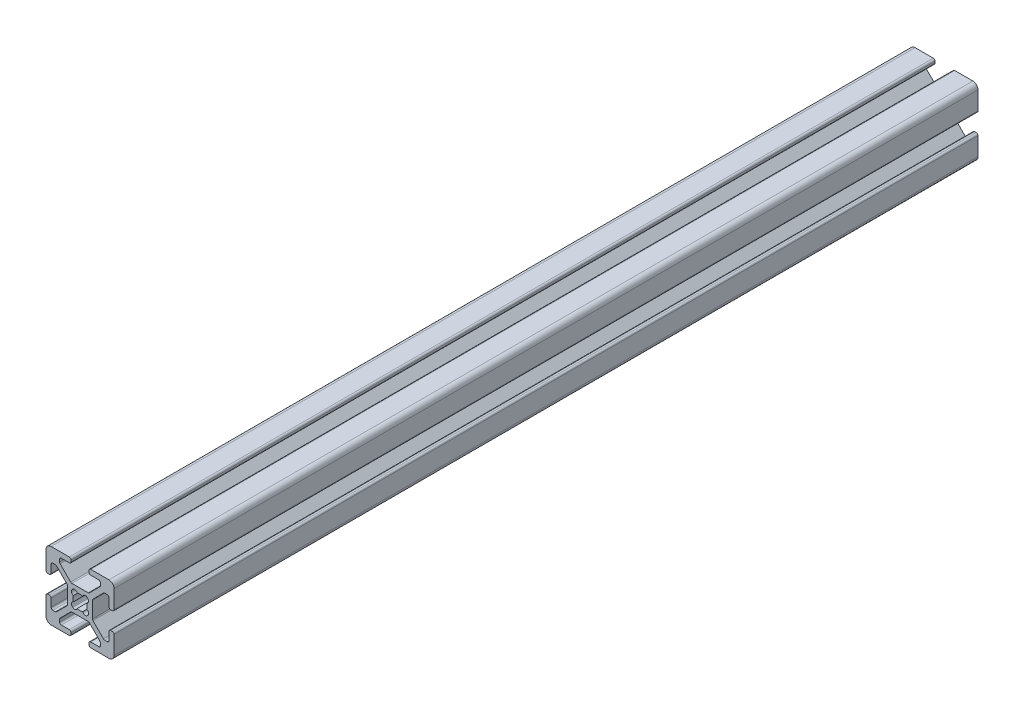
SolidWorks part; units mm, degrees
material "1060 Alloy"
ref_plane "Front Plane" through (0, 0, 0) normal (0, 0, 1) x (1, 0, 0)
ref_plane "Top Plane" through (0, 0, 0) normal (0, 1, 0) x (1, 0, 0)
ref_plane "Right Plane" through (0, 0, 0) normal (1, 0, 0) x (0, 0, -1)
sketch "Sketch2" plane through (0, 0, 0) normal (0, 0, 1) x (1, 0, 0)
  line L0 (-10, -3.138) -> (-10, -8.5)
  line L1 (-8.5, -10) -> (-3.138, -10)
  line L2 (-2.63, -9.492) -> (-2.63, -9.008)
  line L3 (-3.138, -8.5) -> (-5.487, -8.5)
  line L4 (-5.995, -7.992) -> (-5.995, -7.2662)
  line L5 (-5.8462, -6.907) -> (-2.743, -3.8038)
  line L6 (-2.3838, -3.655) -> (2.3841, -3.655)
  line L7 (2.7433, -3.8038) -> (5.8462, -6.9067)
  line L8 (5.995, -7.2659) -> (5.995, -7.992)
  line L9 (5.487, -8.5) -> (3.138, -8.5)
  line L10 (2.63, -9.008) -> (2.63, -9.492)
  line L11 (3.138, -10) -> (8.5, -10)
  line L12 (10, -8.5) -> (10, -3.138)
  line L13 (9.492, -2.63) -> (9.008, -2.63)
  line L14 (8.5, -3.138) -> (8.5, -5.487)
  line L15 (7.992, -5.995) -> (7.2662, -5.995)
  line L16 (6.907, -5.8462) -> (3.8038, -2.743)
  line L17 (3.655, -2.3838) -> (3.655, 2.3841)
  line L18 (3.8038, 2.7433) -> (6.9067, 5.8462)
  line L19 (7.2659, 5.995) -> (7.992, 5.995)
  line L20 (8.5, 5.487) -> (8.5, 3.138)
  line L21 (9.008, 2.63) -> (9.492, 2.63)
  line L22 (10, 3.138) -> (10, 8.5)
  line L23 (8.5, 10) -> (3.138, 10)
  line L24 (2.63, 9.492) -> (2.63, 9.008)
  line L25 (3.138, 8.5) -> (5.487, 8.5)
  line L26 (5.995, 7.992) -> (5.995, 7.2662)
  line L27 (5.8462, 6.907) -> (2.743, 3.8038)
  line L28 (2.3838, 3.655) -> (-2.3841, 3.655)
  line L29 (-2.7433, 3.8038) -> (-5.8462, 6.9067)
  line L30 (-5.995, 7.2659) -> (-5.995, 7.992)
  line L31 (-5.487, 8.5) -> (-3.138, 8.5)
  line L32 (-2.63, 9.008) -> (-2.63, 9.492)
  line L33 (-3.138, 10) -> (-8.5, 10)
  line L34 (-10, 8.5) -> (-10, 3.138)
  line L35 (-9.492, 2.63) -> (-9.008, 2.63)
  line L36 (-8.5, 3.138) -> (-8.5, 5.487)
  line L37 (-7.992, 5.995) -> (-7.2662, 5.995)
  line L38 (-6.907, 5.8462) -> (-3.8038, 2.743)
  line L39 (-3.655, 2.3838) -> (-3.655, -2.3841)
  line L40 (-3.8038, -2.7433) -> (-6.9067, -5.8462)
  line L41 (-7.2659, -5.995) -> (-7.992, -5.995)
  line L42 (-8.5, -5.487) -> (-8.5, -3.138)
  line L43 (-9.008, -2.63) -> (-9.492, -2.63)
  line L44 (-2.1245, 2.3045) -> (-2.3045, 2.1245)
  line L45 (2.3045, 2.1245) -> (2.1245, 2.3045)
  line L46 (2.1245, -2.3045) -> (2.3045, -2.1245)
  line L47 (-2.3045, -2.1245) -> (-2.1245, -2.3045)
  arc A0 (-10, -8.5) -> (-8.5, -10) centre (-8.5, -8.5) ccw
  arc A1 (-3.138, -10) -> (-2.63, -9.492) centre (-3.138, -9.492) ccw
  arc A2 (-2.63, -9.008) -> (-3.138, -8.5) centre (-3.138, -9.008) ccw
  arc A3 (-5.995, -7.992) -> (-5.487, -8.5) centre (-5.487, -7.992) ccw
  arc A4 (-5.8462, -6.907) -> (-5.995, -7.2662) centre (-5.487, -7.2662) ccw
  arc A5 (-2.3838, -3.655) -> (-2.743, -3.8038) centre (-2.3838, -4.163) ccw
  arc A6 (2.7433, -3.8038) -> (2.3841, -3.655) centre (2.3841, -4.163) ccw
  arc A7 (5.995, -7.2659) -> (5.8462, -6.9067) centre (5.487, -7.2659) ccw
  arc A8 (5.487, -8.5) -> (5.995, -7.992) centre (5.487, -7.992) ccw
  arc A9 (3.138, -8.5) -> (2.63, -9.008) centre (3.138, -9.008) ccw
  arc A10 (2.63, -9.492) -> (3.138, -10) centre (3.138, -9.492) ccw
  arc A11 (8.5, -10) -> (10, -8.5) centre (8.5, -8.5) ccw
  arc A12 (10, -3.138) -> (9.492, -2.63) centre (9.492, -3.138) ccw
  arc A13 (9.008, -2.63) -> (8.5, -3.138) centre (9.008, -3.138) ccw
  arc A14 (7.992, -5.995) -> (8.5, -5.487) centre (7.992, -5.487) ccw
  arc A15 (6.907, -5.8462) -> (7.2662, -5.995) centre (7.2662, -5.487) ccw
  arc A16 (3.655, -2.3838) -> (3.8038, -2.743) centre (4.163, -2.3838) ccw
  arc A17 (3.8038, 2.7433) -> (3.655, 2.3841) centre (4.163, 2.3841) ccw
  arc A18 (7.2659, 5.995) -> (6.9067, 5.8462) centre (7.2659, 5.487) ccw
  arc A19 (8.5, 5.487) -> (7.992, 5.995) centre (7.992, 5.487) ccw
  arc A20 (8.5, 3.138) -> (9.008, 2.63) centre (9.008, 3.138) ccw
  arc A21 (9.492, 2.63) -> (10, 3.138) centre (9.492, 3.138) ccw
  arc A22 (10, 8.5) -> (8.5, 10) centre (8.5, 8.5) ccw
  arc A23 (3.138, 10) -> (2.63, 9.492) centre (3.138, 9.492) ccw
  arc A24 (2.63, 9.008) -> (3.138, 8.5) centre (3.138, 9.008) ccw
  arc A25 (5.995, 7.992) -> (5.487, 8.5) centre (5.487, 7.992) ccw
  arc A26 (5.8462, 6.907) -> (5.995, 7.2662) centre (5.487, 7.2662) ccw
  arc A27 (2.3838, 3.655) -> (2.743, 3.8038) centre (2.3838, 4.163) ccw
  arc A28 (-2.7433, 3.8038) -> (-2.3841, 3.655) centre (-2.3841, 4.163) ccw
  arc A29 (-5.995, 7.2659) -> (-5.8462, 6.9067) centre (-5.487, 7.2659) ccw
  arc A30 (-5.487, 8.5) -> (-5.995, 7.992) centre (-5.487, 7.992) ccw
  arc A31 (-3.138, 8.5) -> (-2.63, 9.008) centre (-3.138, 9.008) ccw
  arc A32 (-2.63, 9.492) -> (-3.138, 10) centre (-3.138, 9.492) ccw
  arc A33 (-8.5, 10) -> (-10, 8.5) centre (-8.5, 8.5) ccw
  arc A34 (-10, 3.138) -> (-9.492, 2.63) centre (-9.492, 3.138) ccw
  arc A35 (-9.008, 2.63) -> (-8.5, 3.138) centre (-9.008, 3.138) ccw
  arc A36 (-7.992, 5.995) -> (-8.5, 5.487) centre (-7.992, 5.487) ccw
  arc A37 (-6.907, 5.8462) -> (-7.2662, 5.995) centre (-7.2662, 5.487) ccw
  arc A38 (-3.655, 2.3838) -> (-3.8038, 2.743) centre (-4.163, 2.3838) ccw
  arc A39 (-3.8038, -2.7433) -> (-3.655, -2.3841) centre (-4.163, -2.3841) ccw
  arc A40 (-7.2659, -5.995) -> (-6.9067, -5.8462) centre (-7.2659, -5.487) ccw
  arc A41 (-8.5, -5.487) -> (-7.992, -5.995) centre (-7.992, -5.487) ccw
  arc A42 (-8.5, -3.138) -> (-9.008, -2.63) centre (-9.008, -3.138) ccw
  arc A43 (-9.492, -2.63) -> (-10, -3.138) centre (-9.492, -3.138) ccw
  arc A44 (-1.9358, 0.8037) -> (-1.9358, -0.8037) centre (0, 0) ccw
  arc A45 (-2.3045, 2.1245) -> (-1.9358, 0.8037) centre (-1.748, 1.568) ccw
  arc A46 (-0.8037, 1.9358) -> (-2.1245, 2.3045) centre (-1.568, 1.748) ccw
  arc A47 (0.8037, 1.9358) -> (-0.8037, 1.9358) centre (0, 0) ccw
  arc A48 (2.1245, 2.3045) -> (0.8037, 1.9358) centre (1.568, 1.748) ccw
  arc A49 (1.9358, 0.8037) -> (2.3045, 2.1245) centre (1.748, 1.568) ccw
  arc A50 (1.9358, -0.8037) -> (1.9358, 0.8037) centre (0, 0) ccw
  arc A51 (2.3045, -2.1245) -> (1.9358, -0.8037) centre (1.748, -1.568) ccw
  arc A52 (0.8037, -1.9358) -> (2.1245, -2.3045) centre (1.568, -1.748) ccw
  arc A53 (-0.8037, -1.9358) -> (0.8037, -1.9358) centre (0, 0) ccw
  arc A54 (-2.1245, -2.3045) -> (-0.8037, -1.9358) centre (-1.568, -1.748) ccw
  arc A55 (-1.9358, -0.8037) -> (-2.3045, -2.1245) centre (-1.748, -1.568) ccw
extrude "Boss-Extrude1" add sketch "Sketch2" against normal blind 254
